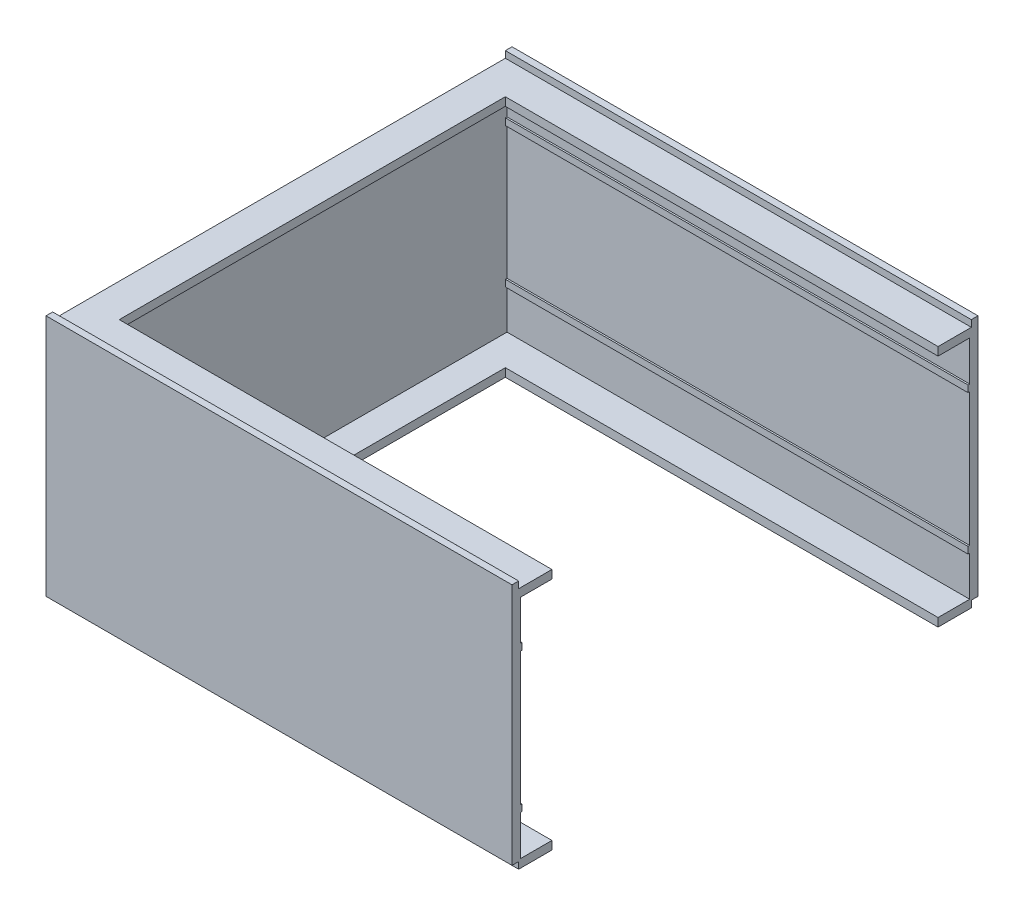
SolidWorks part; units mm, degrees
ref_plane "前视基准面" through (0, 0, 0) normal (0, 0, 1) x (1, 0, 0)
ref_plane "上视基准面" through (0, 0, 0) normal (0, 1, 0) x (1, 0, 0)
ref_plane "右视基准面" through (0, 0, 0) normal (1, 0, 0) x (0, 0, -1)
sketch "草图1" plane through (0, 0, 0) normal (0, 1, 0) x (1, 0, 0)
  line L1 (140, -140) -> (-140, -140)
  line L2 (140, -140) -> (140, 140)
  line L3 (140, 140) -> (-140, 140)
  line L4 (-140, -140) -> (-140, 140)
  line L5 (140, -140) -> (-140, 140) construction
  line L6 (140, 140) -> (-140, -140) construction
  point P0 (0, 0)
  dimension "D1" = 280
  dimension "D2" = 280
extrude "凸台-拉伸1" add sketch "草图1" along normal blind 150
sketch "草图2" plane through (0, 150, 0) normal (0, 1, 0) x (1, 0, 0)
  line L0 (140, -140) -> (140, 140) construction
  line L1 (140, 140) -> (-140, 140) construction
  line L5 (140, -136) -> (-140, -136)
  line L6 (140, -136) -> (140, 136)
  line L7 (140, 136) -> (-140, 136)
  line L8 (-140, -136) -> (-140, 136)
  line L9 (140, -136) -> (-140, 136) construction
  line L10 (140, 136) -> (-140, -136) construction
  point P0 (0, 0)
  dimension "D1" = 0
  dimension "D2" = 4
extrude "切除-拉伸1" cut sketch "草图2" against normal blind 4
sketch "草图3" plane through (0, 0, 0) normal (0, -1, 0) x (1, 0, 0)
  line L0 (-140, 136) -> (140, 136)
  line L1 (-140, -140) -> (-140, 140) construction
  line L2 (140, 140) -> (140, -140) construction
  line L3 (140, -140) -> (-140, -140) construction
  line L4 (-140, 140) -> (140, 140) construction
  line L5 (140, -140) -> (-140, -140)
  line L6 (140, 140) -> (140, 136)
  line L7 (-140, 140) -> (140, 140)
  line L8 (-140, -140) -> (-140, -136)
  line L9 (-140, -136) -> (140, -136)
  line L10 (-140, 136) -> (-140, 140)
  line L11 (140, -136) -> (140, -140)
  dimension "D1" = 4
  dimension "D2" = 4
extrude "切除-拉伸2" cut sketch "草图3" against normal blind 4
sketch "草图4" plane through (140, 0, 0) normal (1, 0, 0) x (0, 0, -1)
  line L0 (0, 146) -> (0, 0) construction
  line L1 (-136, 146) -> (136, 146) construction
  line L2 (-136, 0) -> (136, 0) construction
  line L6 (140, 150) -> (140, 4) construction
  line L7 (135, 5) -> (-135, 5)
  line L8 (135, 5) -> (135, 141)
  line L9 (135, 141) -> (-135, 141)
  line L10 (-135, 5) -> (-135, 141)
  line L11 (135, 5) -> (-135, 141) construction
  line L12 (135, 141) -> (-135, 5) construction
  point P6 (0, 73)
  point P8 (0, 73)
  dimension "D1" = 5
  dimension "D2" = 5
extrude "切除-拉伸3" cut sketch "草图4" against normal offset from surface (278 mm away) 2 up to face at (-140, 75.6667, 0)
sketch "草图6" plane through (0, 146, 0) normal (0, 1, 0) x (1, 0, 0)
  line L11 (140, -136) -> (140, 136) construction
  line L12 (140, 116) -> (-120, 116)
  line L14 (140, 116) -> (140, -116)
  line L15 (140, -116) -> (-120, -116)
  line L16 (-120, 116) -> (-120, -116)
  line L17 (140, 136) -> (-140, 136) construction
  line L18 (-140, -136) -> (140, -136) construction
  line L19 (-140, 136) -> (-140, -136) construction
  dimension "D1" = 20
  dimension "D2" = 20
  dimension "D3" = 20
extrude "切除-拉伸7" cut sketch "草图6" against normal through all
fillet "圆角1" [suppressed] radius 2
sketch "草图7" plane through (0, 0, 0) normal (1, 0, 0) x (0, 0, -1)
  line L0 (-135, 141) -> (-135, 5) construction
  line L1 (-135, 117) -> (-135, 113)
  line L2 (-135, 73) -> (135, 73) construction
  line L3 (135, 141) -> (135, 5) construction
  line L4 (0, 141) -> (0, 5) construction
  line L5 (-135, 141) -> (135, 141) construction
  line L6 (135, 5) -> (-135, 5) construction
  line L7 (-135, 117) -> (-134, 117)
  line L8 (-134, 117) -> (-134, 113)
  line L9 (-134, 113) -> (-135, 113)
  line L10 (-134, 33) -> (-135, 33)
  line L11 (-134, 29) -> (-134, 33)
  line L12 (-135, 29) -> (-134, 29)
  line L13 (-135, 29) -> (-135, 33)
  line L14 (135, 29) -> (135, 33)
  line L15 (135, 29) -> (134, 29)
  line L16 (134, 29) -> (134, 33)
  line L17 (134, 33) -> (135, 33)
  line L18 (134, 113) -> (135, 113)
  line L19 (134, 117) -> (134, 113)
  line L20 (135, 117) -> (134, 117)
  line L21 (135, 117) -> (135, 113)
  dimension "D1" = 1
  dimension "D2" = 4
  dimension "D3" = 40
extrude "凸台-拉伸2" add sketch "草图7" against normal up to surface (278 mm away) from surface at 140 up to face at (-138, 73, 0) starting at face at (140, 74.3333, 129.8333)
